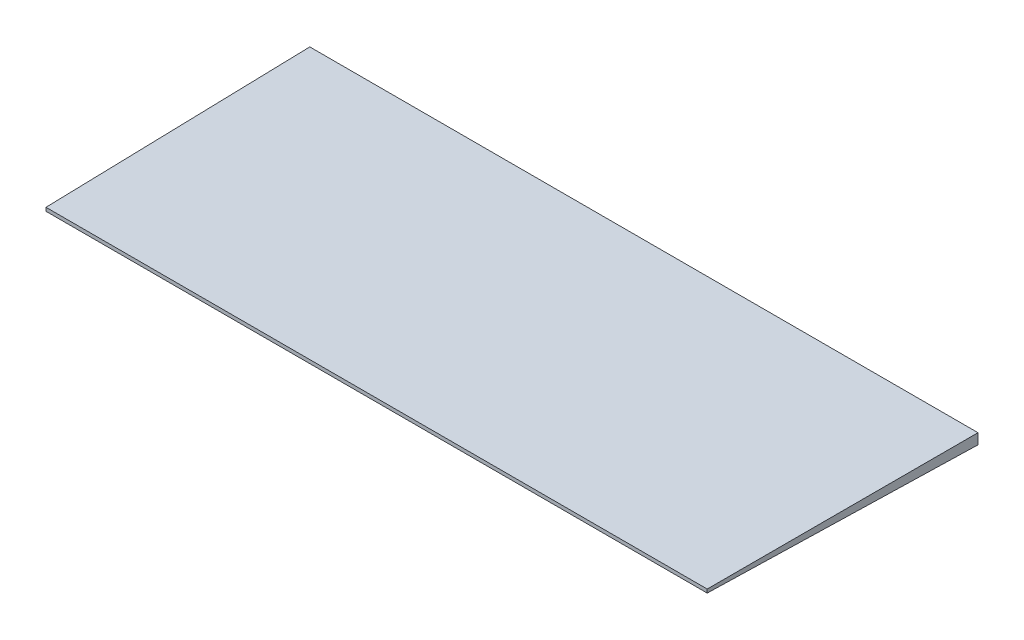
SolidWorks part; units mm, degrees
ref_plane "Front Plane" through (0, 0, 0) normal (0, 0, 1) x (1, 0, 0)
ref_plane "Top Plane" through (0, 0, 0) normal (0, 1, 0) x (1, 0, 0)
ref_plane "Right Plane" through (0, 0, 0) normal (1, 0, 0) x (0, 0, -1)
sketch "Sketch1" plane through (0, 0, 0) normal (0, 0, 1) x (1, 0, 0)
  line L1 (-190.5, -3) -> (190.5, -3)
  line L2 (-190.5, -3) -> (-190.5, 3)
  line L3 (-190.5, 3) -> (190.5, 3)
  line L4 (190.5, -3) -> (190.5, 3)
  line L5 (-190.5, -3) -> (190.5, 3) construction
  line L6 (-190.5, 3) -> (190.5, -3) construction
  point P0 (0, 0)
  dimension "D1" = 6
  dimension "D2" = 381
extrude "Boss-Extrude1" add sketch "Sketch1" along normal blind 152.4 draft 0.75
